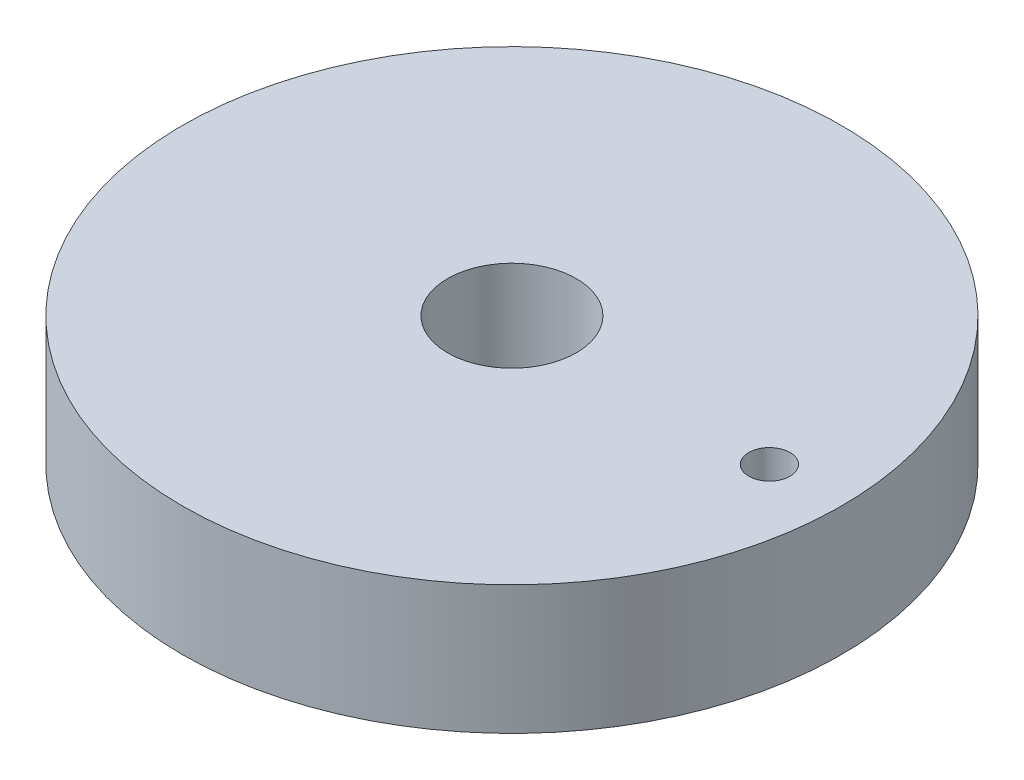
SolidWorks part; units mm, degrees
ref_plane "正面" through (0, 0, 0) normal (0, 0, 1) x (1, 0, 0)
ref_plane "平面" through (0, 0, 0) normal (0, 1, 0) x (1, 0, 0)
ref_plane "右側面" through (0, 0, 0) normal (1, 0, 0) x (0, 0, -1)
sketch "ｽｹｯﾁ1" plane through (0, 0, 0) normal (0, 1, 0) x (1, 0, 0)
  circle A0 centre (0, 0) radius 25.6
  circle A1 centre (20, 0) radius 1.6
  circle A2 centre (0, 0) radius 5
  dimension "D1" = 3.2
  dimension "D3" = 51.2
  dimension "D4" = 10
  dimension "D2" = 20
extrude "ﾎﾞｽ - 押し出し1" add sketch "ｽｹｯﾁ1" along normal blind 10
